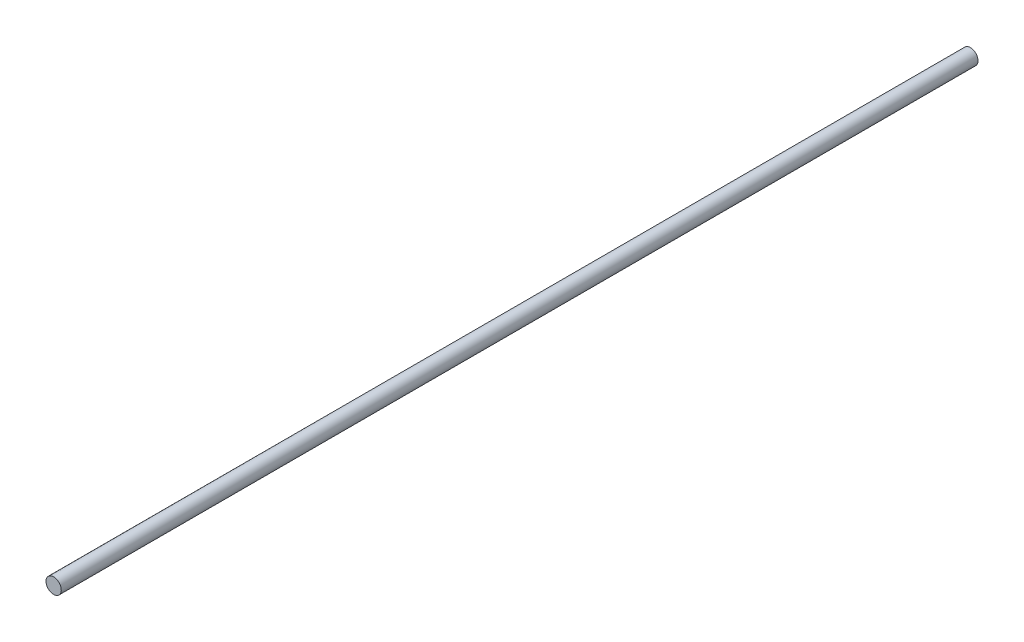
SolidWorks part; units mm, degrees
ref_plane "Front Plane" through (0, 0, 0) normal (0, 0, 1) x (1, 0, 0)
ref_plane "Top Plane" through (0, 0, 0) normal (0, 1, 0) x (1, 0, 0)
ref_plane "Right Plane" through (0, 0, 0) normal (1, 0, 0) x (0, 0, -1)
sketch "Sketch1" plane through (0, 0, 0) normal (0, 0, 1) x (1, 0, 0)
  line L1 (-5, 0) -> (5, 0) construction
  dimension "OD" = 10
sketch "Sketch2" plane through (0, 0, 0) normal (1, 0, 0) x (0, 0, -1)
  line L0 (300, 0) -> (-300, 0)
  point P4 (0, 0)
  dimension "Length" = 600
sketch "Sketch3" plane through (0, 0, 0) normal (0, 0, 1) x (1, 0, 0)
  circle A0 centre (0, 0) radius 5
extrude "Boss-Extrude1" add sketch "Sketch3" along normal up to vertex (300 mm away) and the other way up to vertex (300 mm away) up to point (0, 0, 300) other way up to point (0, 0, -300)
